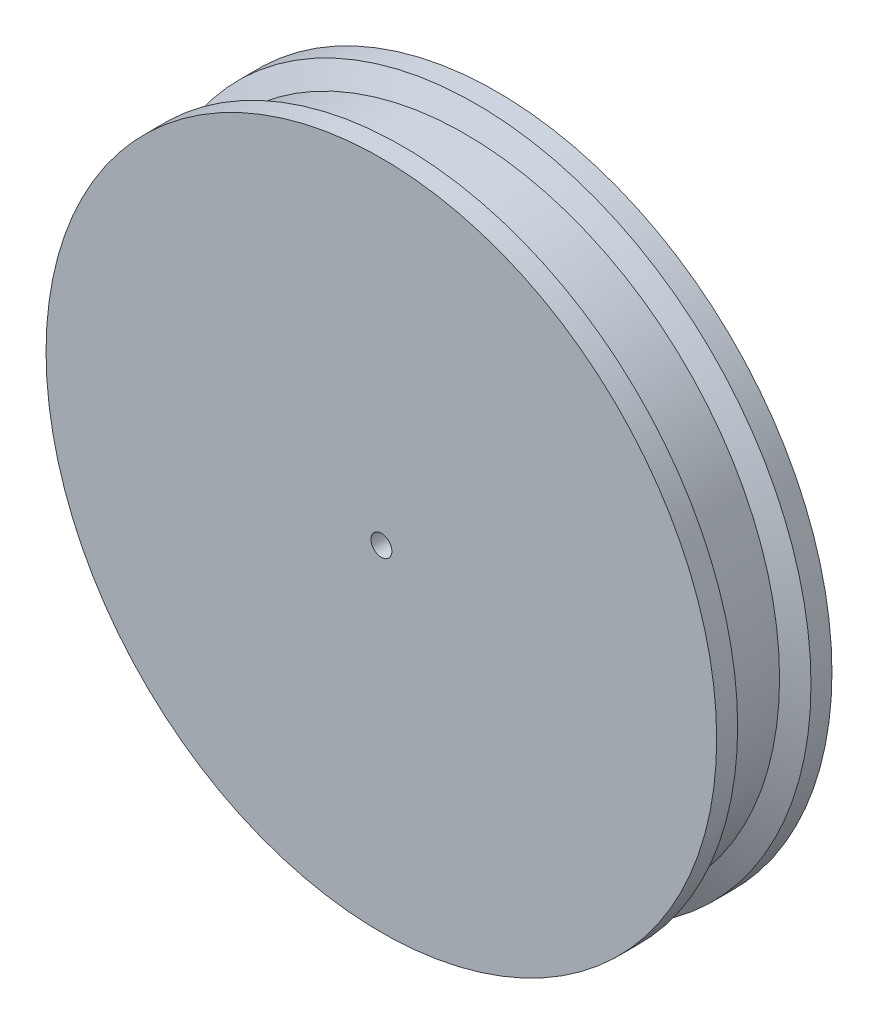
SolidWorks part; units mm, degrees
ref_plane "Front Plane" through (0, 0, 0) normal (0, 0, 1) x (1, 0, 0)
ref_plane "Top Plane" through (0, 0, 0) normal (0, 1, 0) x (1, 0, 0)
ref_plane "Right Plane" through (0, 0, 0) normal (1, 0, 0) x (0, 0, -1)
sketch "Sketch1" plane through (0, 0, 0) normal (0, 0, 1) x (1, 0, 0)
  circle A0 centre (0, 0) radius 32
  circle A1 centre (0, 0) radius 1
  dimension "D1" = 64
  dimension "D2" = 2
extrude "Boss-Extrude1" add sketch "Sketch1" along normal blind 11
sketch "Sketch4" plane through (0, 0, 0) normal (1, 0, 0) x (0, 0, -1)
  line L0 (0, 35.2) -> (0, -35.2) construction
  line L1 (-1000, 0) -> (49000, 0) construction
  line L2 (0, 32) -> (-11, 32) construction
  line L3 (-2, 32) -> (-3, 30)
  line L4 (-3, 30) -> (-8, 30)
  line L5 (-8, 30) -> (-9, 32)
  line L6 (-9, 32) -> (-2, 32)
  line L7 (-5.5, -1000) -> (-5.5, 49000) construction
  line L8 (-11, 32) -> (-11, -32) construction
  point P16 (0, 0)
  dimension "D1" = 5
  dimension "D2" = 5.5
  dimension "D3" = 2
  dimension "D4" = 2
  dimension "D5" = 2
revolve "Cut-Revolve1" cut sketch "Sketch4" angle 360 about L1
